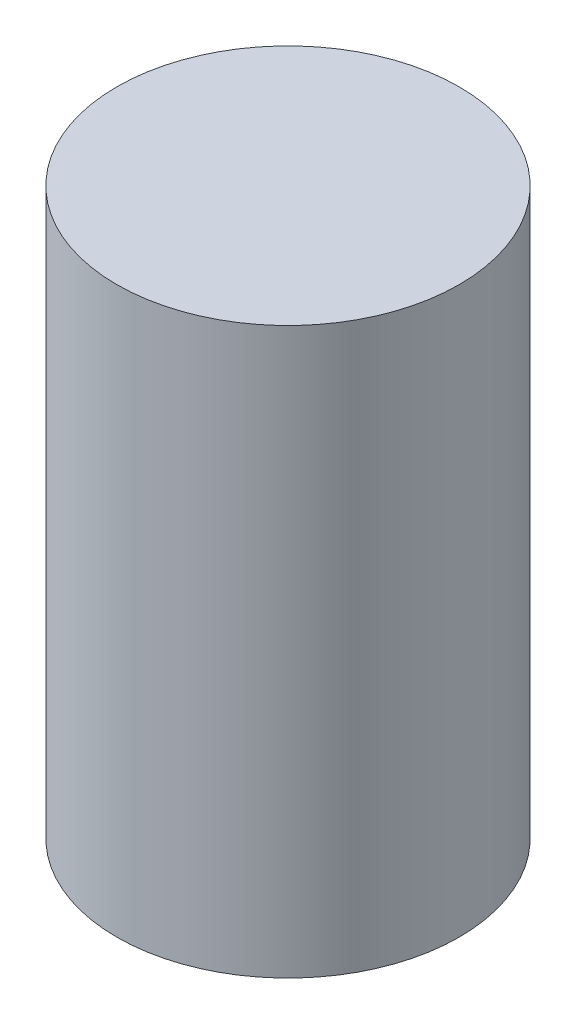
SolidWorks part; units mm, degrees
material "PE High Density"
ref_plane "Front Plane" through (0, 0, 0) normal (0, 0, 1) x (1, 0, 0)
ref_plane "Top Plane" through (0, 0, 0) normal (0, 1, 0) x (1, 0, 0)
ref_plane "Right Plane" through (0, 0, 0) normal (1, 0, 0) x (0, 0, -1)
sketch "Sketch1" plane through (0, 0, 0) normal (0, 1, 0) x (1, 0, 0)
  circle A0 centre (0, 0) radius 50
  dimension "D1" = 100
extrude "Boss-Extrude1" add sketch "Sketch1" along normal blind 165
scale "Scale1" scale about centroid uniform scaling yes scale factor 0.75
